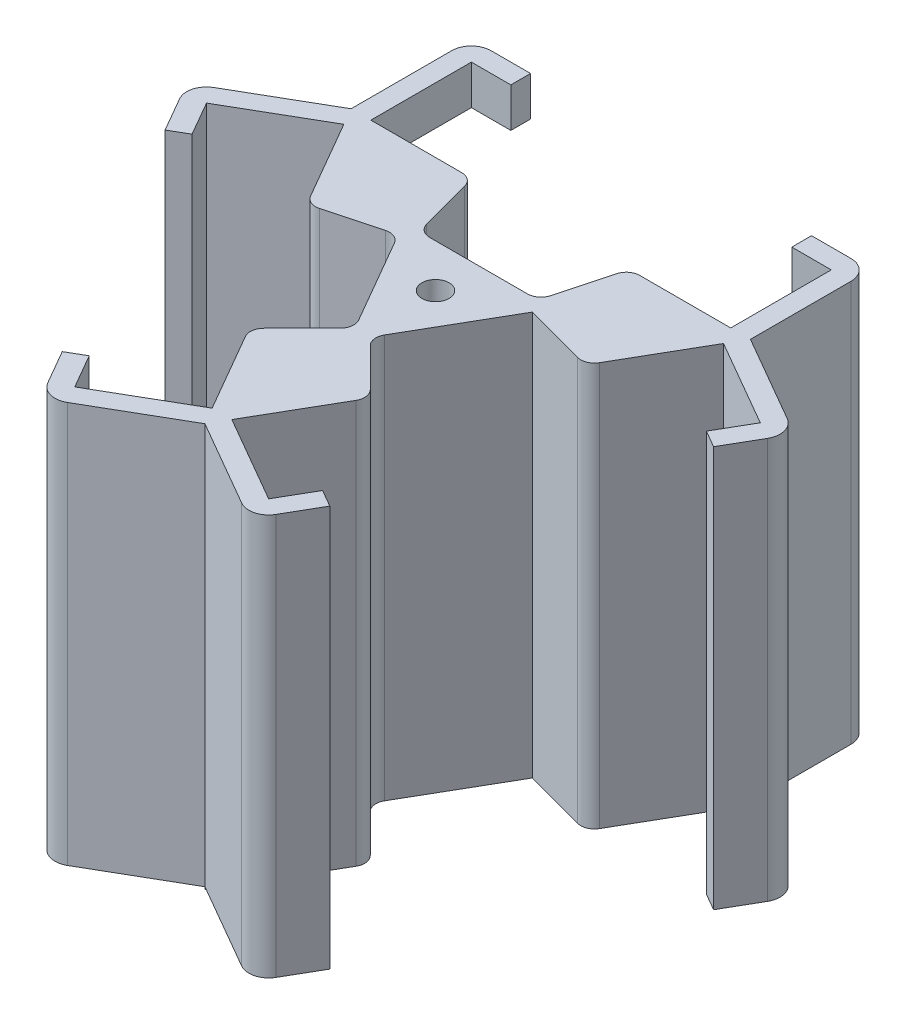
SolidWorks part; units mm, degrees
ref_plane "Alzado" through (0, 0, 0) normal (0, 0, 1) x (1, 0, 0)
ref_plane "Planta" through (0, 0, 0) normal (0, 1, 0) x (1, 0, 0)
ref_plane "Vista lateral" through (0, 0, 0) normal (1, 0, 0) x (0, 0, -1)
sketch "Croquis1" plane through (0, 0, 0) normal (0, 1, 0) x (1, 0, 0)
  line L0 (0, 50.8) -> (0, -50.8) construction
  line L1 (-50.8, 0) -> (50.8, 0) construction
  line L2 (0, 0) -> (-35.921, -35.921) construction
  line L3 (0, 0) -> (35.921, -35.921) construction
  line L10 (0, -17.5) -> (-15.1554, 8.75) construction
  line L11 (-15.1554, 8.75) -> (15.1554, 8.75) construction
  line L12 (15.1554, 8.75) -> (0, -17.5) construction
  line L13 (-1.2978, -16.7522) -> (-15.1813, 7.2027) construction
  line L14 (1.2978, -16.7522) -> (15.1813, 7.2027) construction
  line L15 (-13.8835, 9.4549) -> (13.8835, 9.4549) construction
  line L16 (1.6964, -16.0645) -> (13.335, -27.7031)
  line L17 (13.335, -27.7031) -> (0, -50.8)
  line L18 (0, -50.8) -> (-13.335, -27.7031)
  line L19 (-13.335, -27.7031) -> (-1.6964, -16.0645)
  line L20 (-17.3241, 25.4) -> (-13.0641, 9.5013)
  line L21 (-43.9941, 25.4) -> (-17.3241, 25.4)
  line L22 (-30.6591, 2.3031) -> (-43.9941, 25.4)
  line L23 (-14.7604, 6.5631) -> (-30.6591, 2.3031)
  line L24 (30.6591, 2.3031) -> (14.7604, 6.5631)
  line L25 (43.9941, 25.4) -> (30.6591, 2.3031)
  line L26 (17.3241, 25.4) -> (43.9941, 25.4)
  line L27 (13.0641, 9.5013) -> (17.3241, 25.4)
  line L28 (-14.7604, 6.5631) -> (-1.6964, -16.0645)
  line L29 (1.6964, -16.0645) -> (14.7604, 6.5631)
  line L30 (-13.0641, 9.5013) -> (13.0641, 9.5013)
  line L31 (-43.9941, 25.4) -> (0, -50.8) construction
  line L32 (43.9941, 25.4) -> (0, -50.8) construction
  line L33 (-43.9941, 25.4) -> (43.9941, 25.4) construction
  circle A0 centre (0, 0) radius 50.8 construction
  circle A7 centre (0, 0) radius 17.5 construction
  circle A8 centre (-13.8835, 7.9549) radius 1.5 construction
  circle A9 centre (13.8835, 7.9549) radius 1.5 construction
  circle A10 centre (0, -16) radius 1.5 construction
  arc A11 (-15.1813, 7.2027) -> (-13.8835, 9.4549) centre (-13.8835, 7.9549) cw construction
  arc A12 (15.1813, 7.2027) -> (13.8835, 9.4549) centre (13.8835, 7.9549) ccw construction
  arc A13 (1.2978, -16.7522) -> (-1.2978, -16.7522) centre (0, -16) cw construction
  arc A14 (-15.1813, 7.2027) -> (-13.8835, 9.4549) centre (-13.8835, 7.9549) cw construction
  arc A15 (13.8835, 9.4549) -> (15.1813, 7.2027) centre (13.8835, 7.9549) cw construction
  arc A16 (-1.2978, -16.7522) -> (1.2978, -16.7522) centre (0, -16) ccw construction
  circle A17 centre (0, 0) radius 76.2 construction
  point P45 (0, 0)
  dimension "D1" = 101.6
  dimension "D6" = 13.8835
  dimension "D9" = 3
  dimension "D5" = 3
  dimension "D4" = 35
  dimension "D10" = 152.4
  dimension "D2" = 45
  dimension "D3" = 45
  dimension "D7" = 26.67
extrude "Saliente-Extruir1" add sketch "Croquis1" along normal blind 88.9
sketch "Croquis4" plane through (0, 88.9, 0) normal (0, 1, 0) x (1, 0, 0)
  circle A0 centre (0, 0) radius 3
  dimension "D1" = 6
extrude "Cortar-Extruir1" cut sketch "Croquis4" against normal through all
fillet "Redondeo6" radius 3 5 edges at (-14.7604, 44.45, -6.5631) (1.6964, 44.45, 16.0645) (-1.6964, 44.45, 16.0645) (-13.0641, 44.45, -9.5013) (13.0641, 44.45, -9.5013)
fillet "Redondeo7" radius 3 6 edges at (-17.3241, 44.45, -25.4) (-30.6591, 44.45, -2.3031) (17.3241, 44.45, -25.4) (-13.335, 44.45, 27.7031) (30.6591, 44.45, -2.3031) (13.335, 44.45, 27.7031)
scale "Escala2" scale about centroid uniform scaling yes scale factor 1.15
sketch "Croquis8" plane through (0, 95.5675, 0) normal (0, 1, 0) x (1, 0, 0)
  line L0 (-50.592, 29.2105) -> (-50.592, 54.6878)
  line L1 (-45.592, 59.6878) -> (-35.592, 59.6878)
  line L2 (-35.592, 59.6878) -> (-35.592, 54.6878)
  line L3 (-35.592, 54.6878) -> (-45.592, 54.6878)
  line L4 (-45.592, 54.6878) -> (-45.592, 29.2105)
  line L5 (-22.5688, 29.2105) -> (-50.592, 29.2105) construction
  line L6 (0.0012, 76.2005) -> (0.0012, -76.1995) construction
  line L7 (76.2012, 0.0005) -> (-76.1988, 0.0005) construction
  line L8 (-50.592, 29.2105) -> (-45.592, 29.2105)
  line L9 (50.5944, 29.2105) -> (50.5944, 54.6878)
  line L10 (45.5944, 59.6878) -> (35.5944, 59.6878)
  line L11 (35.5944, 59.6878) -> (35.5944, 54.6878)
  line L12 (35.5944, 54.6878) -> (45.5944, 54.6878)
  line L13 (45.5944, 54.6878) -> (45.5944, 29.2105)
  line L14 (50.5944, 29.2105) -> (45.5944, 29.2105)
  line L15 (50.593, 29.2105) -> (48.093, 24.8804)
  line L16 (70.157, 12.1417) -> (48.093, 24.8804)
  line L17 (65.157, 3.4815) -> (70.157, 12.1417)
  line L18 (69.4871, 0.9815) -> (65.157, 3.4815)
  line L19 (74.4871, 9.6417) -> (69.4871, 0.9815)
  line L20 (50.593, 29.2105) -> (72.657, 16.4718)
  line L21 (-0.0002, -58.4195) -> (22.0638, -71.1582)
  line L22 (28.8939, -69.328) -> (33.8939, -60.6678)
  line L23 (33.8939, -60.6678) -> (29.5638, -58.1678)
  line L24 (29.5638, -58.1678) -> (24.5638, -66.828)
  line L25 (24.5638, -66.828) -> (2.4998, -54.0894)
  line L26 (-0.0002, -58.4195) -> (2.4998, -54.0894)
  line L27 (0.0005, -58.4183) -> (-2.4995, -54.0882)
  line L28 (-24.5635, -66.8268) -> (-2.4995, -54.0882)
  line L29 (-29.5635, -58.1666) -> (-24.5635, -66.8268)
  line L30 (-33.8936, -60.6666) -> (-29.5635, -58.1666)
  line L31 (-28.8936, -69.3268) -> (-33.8936, -60.6666)
  line L32 (0.0005, -58.4183) -> (-22.0635, -71.1569)
  line L33 (-50.5927, 29.2117) -> (-72.6567, 16.4731)
  line L34 (-74.4868, 9.6429) -> (-69.4868, 0.9827)
  line L35 (-69.4868, 0.9827) -> (-65.1567, 3.4827)
  line L36 (-65.1567, 3.4827) -> (-70.1567, 12.1429)
  line L37 (-70.1567, 12.1429) -> (-48.0927, 24.8816)
  line L38 (-50.5927, 29.2117) -> (-48.0927, 24.8816)
  line L44 (-50.592, 29.2105) -> (-36.5804, 4.9417) construction
  circle A0 centre (0.0012, 0.0005) radius 76.2
  arc A1 (-50.592, 54.6878) -> (-45.592, 59.6878) centre (-45.592, 54.6878) cw
  arc A2 (50.5944, 54.6878) -> (45.5944, 59.6878) centre (45.5944, 54.6878) ccw
  arc A3 (72.657, 16.4718) -> (74.4871, 9.6417) centre (70.157, 12.1417) cw
  arc A4 (22.0638, -71.1582) -> (28.8939, -69.328) centre (24.5638, -66.828) ccw
  arc A5 (-22.0635, -71.1569) -> (-28.8936, -69.3268) centre (-24.5635, -66.8268) cw
  arc A6 (-72.6567, 16.4731) -> (-74.4868, 9.6429) centre (-70.1567, 12.1429) ccw
  point P54 (0.0005, 0.0009)
  line M5 (-22.5688, 29.2105) -> (-50.592, 29.2105)
  line M15 (0.0012, -58.4195) -> (14.0128, -34.1507)
  line M22 (36.5828, 4.9417) -> (50.5944, 29.2105)
  line M23 (50.5944, 29.2105) -> (22.5712, 29.2105)
  dimension "D1" = 152.4
  dimension "D2" = 5
  dimension "D3" = 10
  dimension "D6" = 50.5918
  dimension "D4" = 3
extrude "Saliente-Extruir3" add sketch "Croquis8" against normal blind 101.6 contours A1 L0 L4 L3 L2 L1 M5 | L33 A6 A0 L34 L35 L36 L37 L38 | A5 A0 L32 L27 L28 L29 L30 L31 | A0 A4 L22 L23 L24 L25 L26 L21 M15 | A3 L20 L16 L17 L18 L19 M22 | L9 A2 L10 L11 L12 L13 M23
sketch "Croquis9" plane through (0, 95.5675, 0) normal (0, 1, 0) x (1, 0, 0)
  circle A0 centre (0, 0) radius 101.6
  circle A1 centre (0, 0) radius 76.2
  dimension "D1" = 152.4
  dimension "D2" = 203.2
sketch "Croquis10" plane through (-50.592, 0, 0) normal (-1, 0, 0) x (0, 0, 1)
  line L0 (-29.2105, 95.5675) -> (-29.2105, -6.0325) construction
  line L1 (-29.2105, 85.5675) -> (-61.2105, 85.5675)
  line L2 (-29.2105, 85.5675) -> (-29.2105, 3.9675)
  line L3 (-29.2105, 3.9675) -> (-61.2105, 3.9675)
  line L4 (-61.2105, 85.5675) -> (-61.2105, 3.9675)
  line L5 (101.6, 95.5675) -> (-101.6, 95.5675) construction
  line L6 (-29.2105, -6.0325) -> (-54.6878, -6.0325) construction
  dimension "D1" = 10
  dimension "D2" = 10
  dimension "D3" = 32
extrude "Cortar-Extruir2" cut sketch "Croquis10" against normal blind 15
